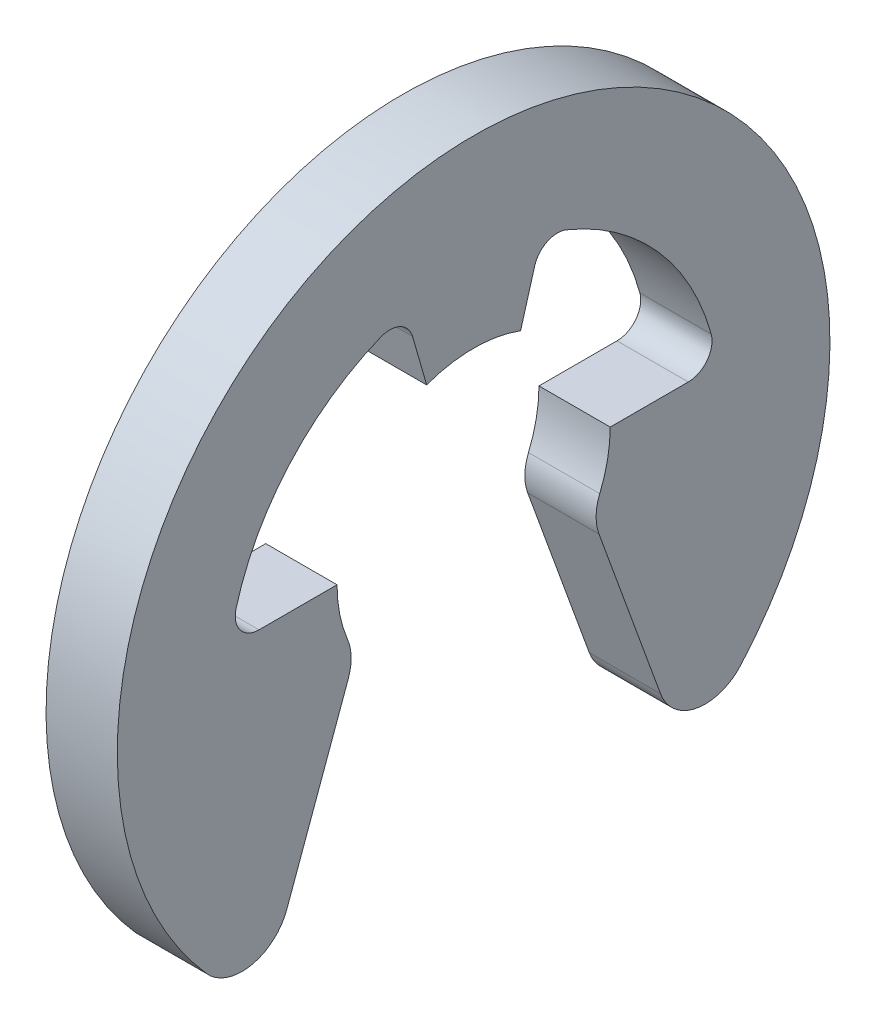
SolidWorks part; units mm, degrees
material "Acier allié"
ref_plane "Plan1" through (0, 0, 0) normal (0, 0, 1) x (1, 0, 0)
ref_plane "Plan2" through (0, 0, 0) normal (0, 1, 0) x (1, 0, 0)
ref_plane "Plan3" through (0, 0, 0) normal (1, 0, 0) x (0, 0, -1)
sketch "Esquisse1" plane through (0, 0, 0) normal (1, 0, 0) x (0, 0, -1)
  line L0 (0, 0) -> (1.7775, -2.4167) construction
  line L1 (0, 0) -> (0, -9.1601) construction
  line L2 (-20, 0) -> (20, 0) construction
  line L3 (0, 0) -> (0.8269, 2.8838) construction
  line L4 (-20, 0.3) -> (20, 0.3) construction
  line L5 (0.3957, 1.3798) -> (1.7775, -2.4167) construction
  line L6 (0.3957, 1.3798) -> (0.5139, 1.7921)
  line L7 (-1.15, 0.3) -> (-1.8071, 0.3)
  line L8 (1.0552, -0.4323) -> (1.5737, -1.857)
  line L9 (1.15, 0.3) -> (1.8071, 0.3)
  line L10 (-1.0552, -0.4323) -> (-1.5737, -1.857)
  line L11 (-0.3957, 1.3798) -> (-0.5139, 1.7921)
  arc A0 (2.2496, -1.9848) -> (-2.2496, -1.9848) centre (0, 0) ccw
  arc A1 (1.9999, 0.5533) -> (0.7814, 1.9222) centre (0, 0) ccw
  arc A2 (0.3957, 1.3798) -> (-0.3957, 1.3798) centre (0, 0.3) ccw
  arc A3 (1.15, 0.3) -> (1.0618, -0.1418) centre (0, 0.3) cw
  arc A4 (2.2496, -1.9848) -> (1.5737, -1.857) centre (1.9496, -1.7202) cw
  arc A5 (0.7814, 1.9222) -> (0.5139, 1.7921) centre (0.7061, 1.737) ccw
  arc A6 (1.9999, 0.5533) -> (1.8071, 0.3) centre (1.8071, 0.5) cw
  arc A7 (-1.9999, 0.5533) -> (-1.8071, 0.3) centre (-1.8071, 0.5) ccw
  arc A8 (-0.7814, 1.9222) -> (-0.5139, 1.7921) centre (-0.7061, 1.737) cw
  arc A9 (-2.2496, -1.9848) -> (-1.5737, -1.857) centre (-1.9496, -1.7202) ccw
  arc A10 (-1.15, 0.3) -> (-1.0618, -0.1418) centre (0, 0.3) ccw
  arc A11 (-1.9999, 0.5533) -> (-0.7814, 1.9222) centre (0, 0) cw
  arc A12 (1.0552, -0.4323) -> (1.0618, -0.1418) centre (1.4311, -0.2955) cw
  arc A13 (-1.0552, -0.4323) -> (-1.0618, -0.1418) centre (-1.4311, -0.2955) ccw
  point P24 (0.5719, 1.9946)
  dimension "D1" = 3
  dimension "D3" = 2.075
  dimension "D4" = 0.4
  dimension "D7" = 0.4
  dimension "D2" = 0.3
  dimension "D8" = 16
  dimension "D9" = 20
extrude "Base-Extrusion" add sketch "Esquisse1" along normal blind 0.6
equation "\"r@Esquisse1\"=\"D1@Base-Extrusion\"/3"
equation "\"D3@Esquisse1\" = (\"D1@Esquisse1\"+\"dn@Esquisse1\")/2"
equation "\"D4@Esquisse1\"=\"r@Esquisse1\"*2"
equation "\"D2@Esquisse1\"=\"D1@Base-Extrusion\"/2"
